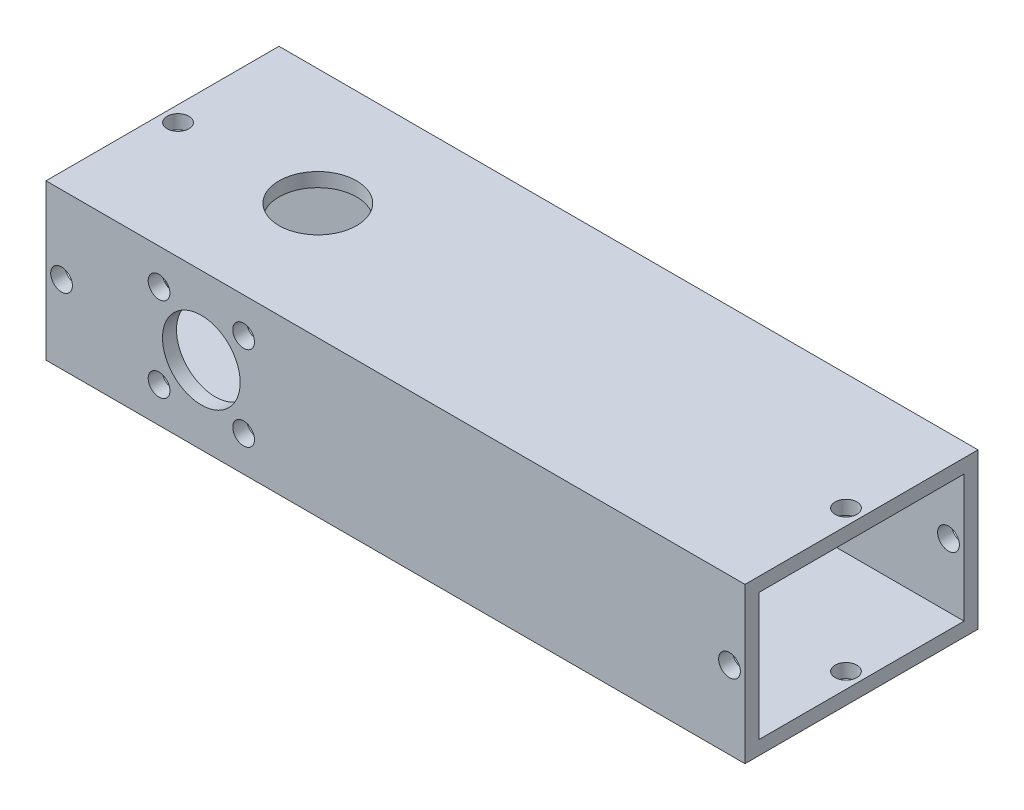
SolidWorks part; units mm, degrees
ref_plane "Front Plane" through (0, 0, 0) normal (0, 0, 1) x (1, 0, 0)
ref_plane "Top Plane" through (0, 0, 0) normal (0, 1, 0) x (1, 0, 0)
ref_plane "Right Plane" through (0, 0, 0) normal (1, 0, 0) x (0, 0, -1)
sketch "Sketch1" plane through (0, 0, 0) normal (0, 1, 0) x (1, 0, 0)
  line L1 (0, 0) -> (-114.3, 0)
  line L2 (0, 0) -> (0, -38.1)
  line L3 (0, -38.1) -> (-114.3, -38.1)
  line L4 (-114.3, 0) -> (-114.3, -38.1)
  dimension "D1" = 114.3
  dimension "D2" = 38.1
extrude "Boss-Extrude1" add sketch "Sketch1" along normal blind 25.4
sketch "Sketch2" plane through (0, 0, 0) normal (1, 0, 0) x (0, 0, -1)
  line L0 (0, 0) -> (-2.286, 0) construction
  line L1 (-38.1, 0) -> (0, 0) construction
  line L2 (-2.286, 0) -> (-2.286, 2.286) construction
  line L4 (-2.286, 2.286) -> (-35.814, 2.286)
  line L5 (-2.286, 2.286) -> (-2.286, 23.114)
  line L6 (-2.286, 23.114) -> (-35.814, 23.114)
  line L7 (-35.814, 2.286) -> (-35.814, 23.114)
  dimension "D1" = 20.828
  dimension "D2" = 33.528
extrude "Cut-Extrude1" cut sketch "Sketch2" against normal up to next
sketch "Sketch3" plane through (0, 0, 38.1) normal (0, 0, 1) x (1, 0, 0)
  line L0 (0, 0) -> (0, 12.7) construction
  line L1 (0, 25.4) -> (0, 0) construction
  line L2 (0, 12.7) -> (-2.54, 12.7) construction
  circle A0 centre (-2.54, 12.7) radius 1.778
extrude "Cut-Extrude2" cut sketch "Sketch3" against normal up to next
sketch "Sketch4" plane through (0, 0, 0) normal (0, 0, -1) x (-1, 0, 0)
  line L0 (0, 0) -> (0, 12.7) construction
  line L1 (0, 25.4) -> (0, 0) construction
  line L2 (0, 12.7) -> (2.54, 12.7) construction
  circle A0 centre (2.54, 12.7) radius 1.778
extrude "Cut-Extrude3" cut sketch "Sketch4" against normal up to next
sketch "Sketch5" plane through (0, 0, 38.1) normal (0, 0, 1) x (1, 0, 0)
  line L0 (-114.3, 0) -> (-114.3, 12.7) construction
  line L1 (-114.3, 25.4) -> (-114.3, 0) construction
  line L2 (-114.3, 12.7) -> (-111.76, 12.7) construction
  line L3 (-114.3, 12.7) -> (-88.9, 12.7) construction
  line L4 (-88.9, 12.7) -> (-81.9852, 19.6148) construction
  line L5 (-88.9, 12.7) -> (-95.8148, 5.7852) construction
  line L6 (-88.9, 12.7) -> (-81.9852, 5.7852) construction
  line L7 (-88.9, 12.7) -> (-95.8148, 19.6148) construction
  circle A0 centre (-111.76, 12.7) radius 1.778
  circle A1 centre (-88.9, 12.7) radius 6.35
  circle A2 centre (-95.8148, 19.6148) radius 1.778
  circle A3 centre (-81.9852, 19.6148) radius 1.778
  circle A4 centre (-95.8148, 5.7852) radius 1.778
  circle A5 centre (-81.9852, 5.7852) radius 1.778
  dimension "D1" = 12.7
  dimension "D2" = 3.556
extrude "Cut-Extrude4" cut sketch "Sketch5" against normal up to next
sketch "Sketch6" plane through (0, 0, 0) normal (0, 0, -1) x (-1, 0, 0)
  line L0 (114.3, 0) -> (114.3, 12.7) construction
  line L1 (114.3, 25.4) -> (114.3, 0) construction
  line L2 (114.3, 12.7) -> (111.76, 12.7) construction
  line L3 (114.3, 12.7) -> (88.9, 12.7) construction
  line L4 (88.9, 12.7) -> (81.9852, 5.7852) construction
  line L5 (88.9, 12.7) -> (95.8148, 19.6148) construction
  line L6 (88.9, 12.7) -> (95.8148, 5.7852) construction
  line L7 (88.9, 12.7) -> (81.9852, 19.6148) construction
  circle A0 centre (111.76, 12.7) radius 1.778
  circle A1 centre (88.9, 12.7) radius 6.35
  circle A2 centre (81.9852, 19.6148) radius 1.778
  circle A3 centre (95.8148, 19.6148) radius 1.778
  circle A4 centre (95.8148, 5.7852) radius 1.778
  circle A5 centre (81.9852, 5.7852) radius 1.778
  dimension "D1" = 12.7
extrude "Cut-Extrude5" cut sketch "Sketch6" against normal up to next
sketch "Sketch7" plane through (0, 25.4, 0) normal (0, 1, 0) x (1, 0, 0)
  line L0 (-114.3, -38.1) -> (-114.3, -19.05) construction
  line L1 (-114.3, 0) -> (-114.3, -38.1) construction
  line L2 (-114.3, -19.05) -> (-111.76, -19.05) construction
  line L3 (-114.3, -19.05) -> (-88.9, -19.05) construction
  circle A0 centre (-111.76, -19.05) radius 1.778
  circle A1 centre (-88.9, -19.05) radius 6.35
  dimension "D1" = 12.7
extrude "Cut-Extrude6" cut sketch "Sketch7" against normal up to next
sketch "Sketch8" plane through (0, 0, 0) normal (0, -1, 0) x (1, 0, 0)
  line L0 (-114.3, 38.1) -> (-114.3, 19.05) construction
  line L1 (-114.3, 0) -> (-114.3, 38.1) construction
  line L2 (-114.3, 19.05) -> (-111.76, 19.05) construction
  line L3 (-114.3, 19.05) -> (-88.9, 19.05) construction
  circle A0 centre (-111.76, 19.05) radius 1.778
  circle A1 centre (-88.9, 19.05) radius 6.35
  dimension "D1" = 12.7
extrude "Cut-Extrude7" cut sketch "Sketch8" against normal up to next
sketch "Sketch9" plane through (0, 25.4, 0) normal (0, 1, 0) x (1, 0, 0)
  line L0 (0, -38.1) -> (0, -19.05) construction
  line L1 (0, -38.1) -> (0, 0) construction
  line L2 (0, -19.05) -> (-2.54, -19.05) construction
  circle A0 centre (-2.54, -19.05) radius 1.778
extrude "Cut-Extrude8" cut sketch "Sketch9" against normal up to next
sketch "Sketch10" plane through (0, 0, 0) normal (0, -1, 0) x (-1, 0, 0)
  line L0 (0, -38.1) -> (0, -19.05) construction
  line L1 (0, -38.1) -> (0, 0) construction
  line L2 (0, -19.05) -> (2.54, -19.05) construction
  circle A0 centre (2.54, -19.05) radius 1.778
extrude "Cut-Extrude9" cut sketch "Sketch10" against normal up to next
sketch "Sketch11" plane through (0, 25.4, 0) normal (0, 1, 0) x (1, 0, 0)
